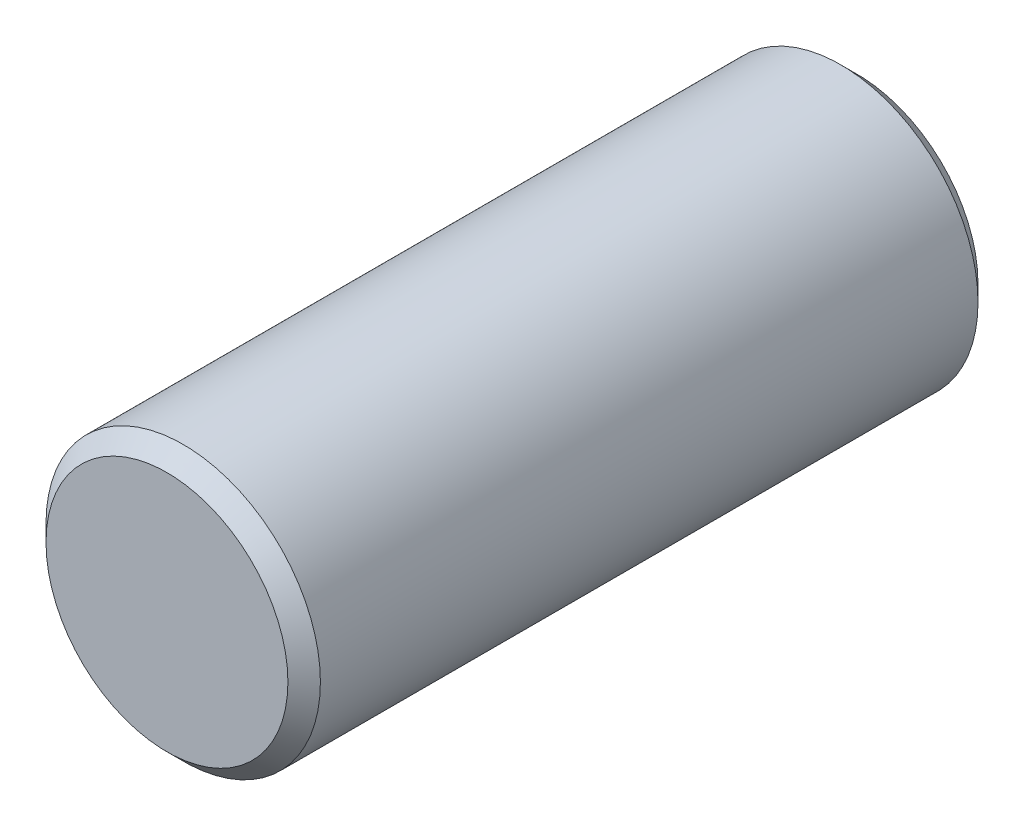
SolidWorks part; units mm, degrees
ref_plane "Front Plane" through (0, 0, 0) normal (0, 0, 1) x (1, 0, 0)
ref_plane "Top Plane" through (0, 0, 0) normal (0, 1, 0) x (1, 0, 0)
ref_plane "Right Plane" through (0, 0, 0) normal (1, 0, 0) x (0, 0, -1)
sketch "Sketch1" plane through (0, 0, 0) normal (0, 0, 1) x (1, 0, 0)
  circle A0 centre (0, 0) radius 16.9
extrude "Boss-Extrude1" add sketch "Sketch1" along normal mid plane 85
chamfer "Chamfer1" distance 2 angle 45 1 edges at (16.9, 0, 42.5)
chamfer "Chamfer2" distance 2 angle 45 1 edges at (16.9, 0, -42.5)
